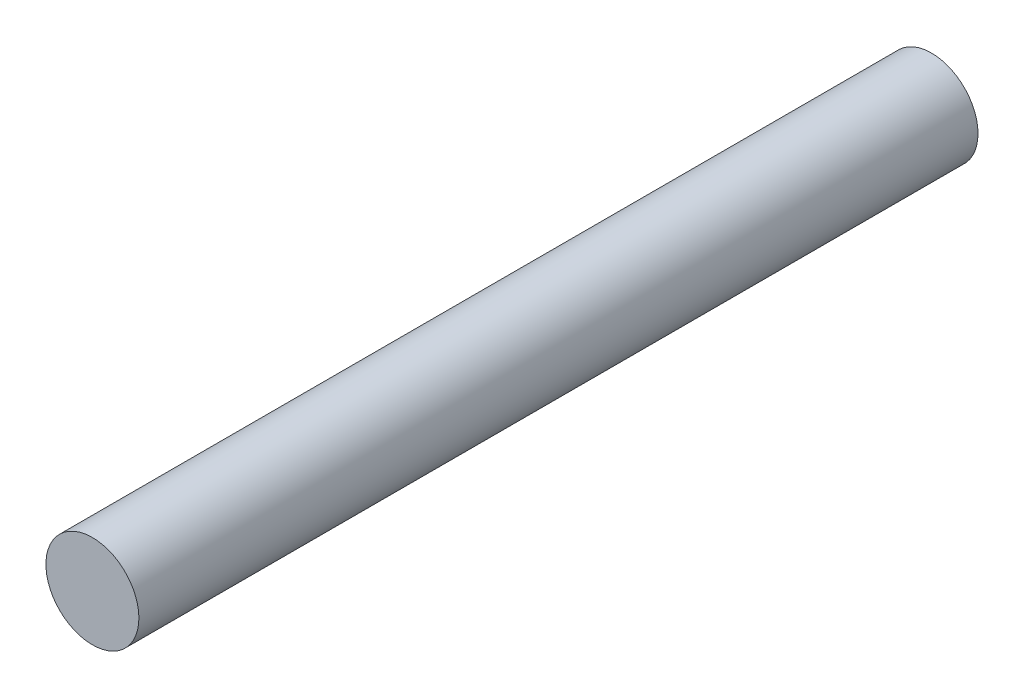
SolidWorks part; units mm, degrees
material "6061 Alloy"
ref_plane "Front Plane" through (0, 0, 0) normal (0, 0, 1) x (1, 0, 0)
ref_plane "Top Plane" through (0, 0, 0) normal (0, 1, 0) x (1, 0, 0)
ref_plane "Right Plane" through (0, 0, 0) normal (1, 0, 0) x (0, 0, -1)
sketch "Sketch1" plane through (0, 0, 0) normal (0, 0, 1) x (1, 0, 0)
  circle A0 centre (0, 0) radius 2.05
  dimension "D1" = 4.1
extrude "Boss-Extrude1" add sketch "Sketch1" along normal blind 37
